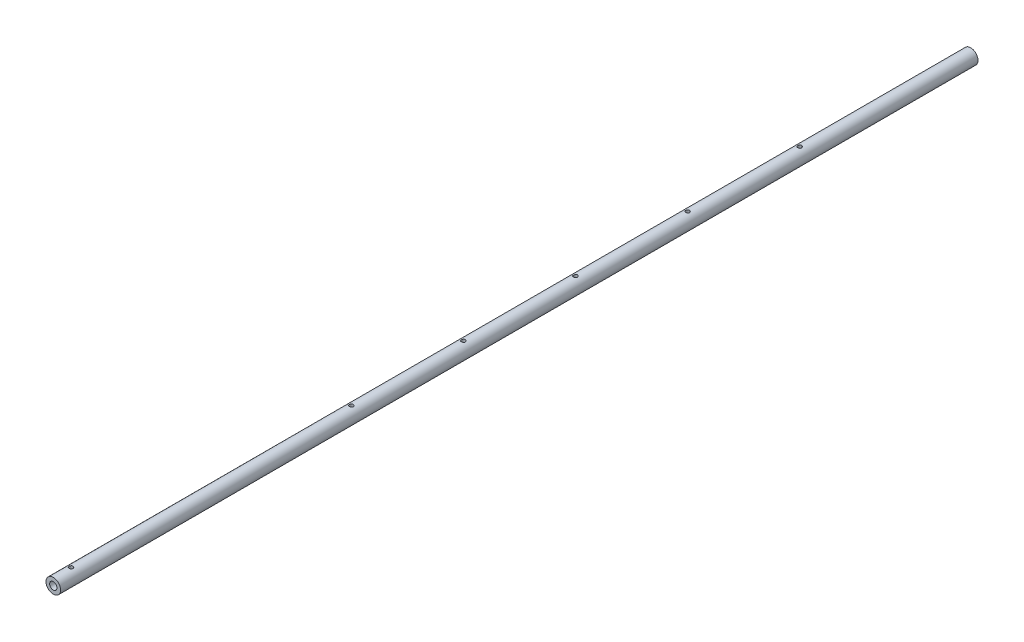
SolidWorks part; units mm, degrees
ref_plane "Front Plane" through (0, 0, 0) normal (0, 0, 1) x (1, 0, 0)
ref_plane "Top Plane" through (0, 0, 0) normal (0, 1, 0) x (1, 0, 0)
ref_plane "Right Plane" through (0, 0, 0) normal (1, 0, 0) x (0, 0, -1)
sketch "Sketch1" plane through (0, 0, 0) normal (0, 0, 1) x (1, 0, 0)
  circle A0 centre (0, 0) radius 3.9306
  circle A1 centre (0, 0) radius 7.8613
  dimension "D1" = 15.7226
  dimension "D2" = 7.8613
extrude "Rod" add sketch "Sketch1" along normal blind 987.425 contours A0
sketch "Sketch3" plane through (0, 0, 0) normal (0, 1, 0) x (1, 0, 0)
  line L0 (0, -666.75) -> (0, -962.025) construction
  line L1 (-7.8613, -987.425) -> (7.8613, -987.425) construction
  circle A0 centre (0, -184.15) radius 2.1082
  circle A4 centre (0, -304.8) radius 2.1082
  circle A8 centre (0, -425.45) radius 2.1082
  circle A11 centre (0, -546.1) radius 2.1082
  circle A12 centre (0, -666.75) radius 2.1082
  circle A13 centre (0, -968.375) radius 2.1082
  dimension "D1" = 4.2164
  dimension "D6" = 4.2164
  dimension "D2" = 184.15
  dimension "D4" = 120.65
  dimension "D5" = 295.275
  dimension "D7" = 19.05
  dimension "D3" = 5
extrude "Holes" cut sketch "Sketch3" against normal through all both and the other way through all
ref_plane "Handle Location" through (0, 0, 962.025) normal (0, 0, 1) x (1, 0, 0)
equation "\"L\"= 38.875"
equation "\"D1@Rod\" = \"L\""
equation "\"N\"= 5"
equation "\"D3@Sketch3\"=\"N\""
equation "\"S\"= 4.75"
equation "\"D4@Sketch3\"=\"S\""
equation "\"O\"= 7.25"
equation "\"D2@Sketch3\"=\"O\""
equation "\"H\"= 11.625"
equation "\"D5@Sketch3\"=\"H\""
